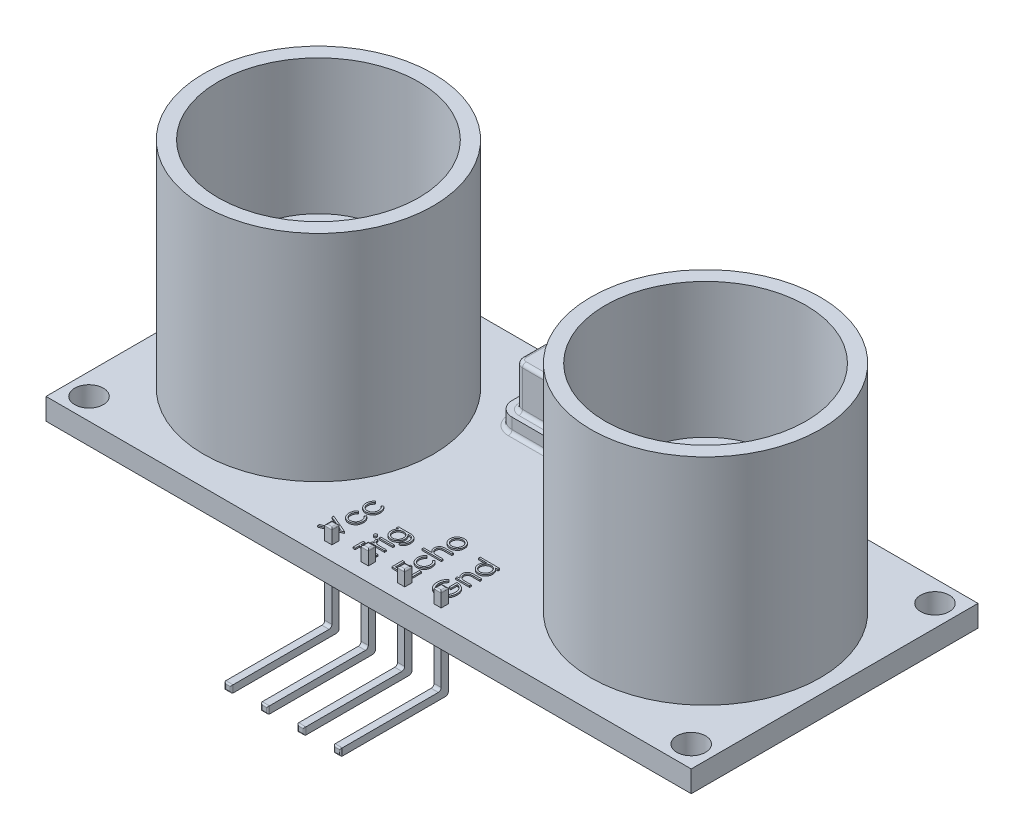
SolidWorks part; units mm, degrees
ref_plane "Front Plane" through (0, 0, 0) normal (0, 0, 1) x (1, 0, 0)
ref_plane "Top Plane" through (0, 0, 0) normal (0, 1, 0) x (1, 0, 0)
ref_plane "Right Plane" through (0, 0, 0) normal (1, 0, 0) x (0, 0, -1)
sketch "Sketch1" plane through (0, 0, 0) normal (0, 1, 0) x (1, 0, 0)
  line L0 (0, 10) -> (45, 10) construction
  line L1 (0, 0) -> (45, 0)
  line L2 (0, 0) -> (0, 20)
  line L3 (0, 20) -> (45, 20)
  line L4 (45, 0) -> (45, 20)
  line L5 (22.5, 20) -> (22.5, 0) construction
  circle A0 centre (1.5, 18.5) radius 1
  circle A1 centre (43.5, 18.5) radius 1
  circle A2 centre (43.5, 1.5) radius 1
  circle A3 centre (1.5, 1.5) radius 1
  dimension "D3" = 2
  dimension "D4" = 1.5
  dimension "D5" = 1.5
  dimension "D1" = 20
  dimension "D2" = 45
extrude "Boss-Extrude1" add sketch "Sketch1" along normal blind 1.5
sketch "Sketch2" plane through (0, 1.5, 0) normal (0, 1, 0) x (1, 0, 0)
  line L0 (45, 20) -> (0, 20) construction
  line L1 (18.5, 19) -> (26.5, 19)
  line L2 (17.5, 18) -> (17.5, 15)
  line L3 (18.5, 14) -> (26.5, 14)
  line L4 (27.5, 18) -> (27.5, 15)
  line L5 (22.5, 20) -> (22.5, 0) construction
  line L6 (0, 0) -> (45, 0) construction
  arc A0 (27.5, 18) -> (26.5, 19) centre (26.5, 18) ccw
  arc A1 (26.5, 14) -> (27.5, 15) centre (26.5, 15) ccw
  arc A2 (17.5, 15) -> (18.5, 14) centre (18.5, 15) ccw
  arc A3 (18.5, 19) -> (17.5, 18) centre (18.5, 18) ccw
  point P15 (22.5, 19)
  dimension "D1" = 1
  dimension "D2" = 10
  dimension "D3" = 5
  dimension "D4" = 1
extrude "Boss-Extrude2" add sketch "Sketch2" along normal blind 1
sketch "Sketch4" plane through (0, 2.5, 0) normal (0, 1, 0) x (1, 0, 0)
  line L1 (18.6475, 18.4133) -> (26.3525, 18.4133)
  line L2 (18.1475, 17.9133) -> (18.1475, 15.0867)
  line L3 (18.6475, 14.5867) -> (26.3525, 14.5867)
  line L4 (26.8525, 17.9133) -> (26.8525, 15.0867)
  line L5 (22.5, 19) -> (22.5, 14) construction
  line L6 (18.5, 19) -> (26.5, 19) construction
  line L7 (18.5, 14) -> (26.5, 14) construction
  line L8 (17.5, 16.5) -> (27.5, 16.5) construction
  line L9 (17.5, 18) -> (17.5, 15) construction
  line L10 (27.5, 18) -> (27.5, 15) construction
  arc A0 (26.3525, 18.4133) -> (26.8525, 17.9133) centre (26.3525, 17.9133) cw
  arc A1 (26.8525, 15.0867) -> (26.3525, 14.5867) centre (26.3525, 15.0867) cw
  arc A2 (18.6475, 14.5867) -> (18.1475, 15.0867) centre (18.6475, 15.0867) cw
  arc A3 (18.6475, 18.4133) -> (18.1475, 17.9133) centre (18.6475, 17.9133) ccw
  point P10 (22.5, 18.4133)
  point P17 (26.8525, 16.5)
  dimension "D1" = 0.5
extrude "Boss-Extrude3" add sketch "Sketch4" along normal blind 3
fillet "Fillet1" radius 0.25 24 edges at (18.294, 5.5, -14.7331) (18.1475, 5.5, -16.5) (18.294, 5.5, -18.2669) (22.5, 5.5, -18.4133) (26.706, 5.5, -18.2669) (26.8525, 5.5, -16.5) (26.706, 5.5, -14.7331) (17.7929, 1.5, -14.2929) (17.5, 1.5, -16.5) (17.7929, 1.5, -18.7071) (22.5, 1.5, -19) (27.2071, 1.5, -18.7071) (27.5, 1.5, -16.5) (27.2071, 1.5, -14.2929) (18.294, 2.5, -18.2669) (22.5, 2.5, -18.4133) (26.706, 2.5, -18.2669) (26.8525, 2.5, -16.5) (26.706, 2.5, -14.7331) (22.5, 2.5, -14.5867) (18.294, 2.5, -14.7331) (22.5, 5.5, -14.5867) (22.5, 1.5, -14) (18.1475, 2.5, -16.5)
sketch "Sketch5" plane through (0, 1.5, 0) normal (0, 1, 0) x (1, 0, 0)
  line L0 (0, 10) -> (45, 10) construction
  line L1 (0, 20) -> (0, 0) construction
  line L2 (45, 0) -> (45, 20) construction
  line L3 (22.5, 20) -> (22.5, 0) construction
  line L4 (45, 20) -> (0, 20) construction
  line L5 (0, 0) -> (45, 0) construction
  circle A0 centre (9, 10) radius 8
  circle A1 centre (36, 10) radius 8
  dimension "D1" = 16
  dimension "D2" = 9
extrude "Boss-Extrude4" add sketch "Sketch5" along normal blind 15
sketch "Sketch6" plane through (0, 16.5, 0) normal (0, 1, 0) x (1, 0, 0)
  line L0 (1, 10) -> (44, 10) construction
  line L1 (9, 18) -> (9, 2) construction
  line L2 (36, 18) -> (36, 2) construction
  line L3 (22.5, 20) -> (22.5, 0) construction
  line L4 (45, 20) -> (0, 20) construction
  line L5 (0, 0) -> (45, 0) construction
  circle A0 centre (9, 10) radius 8 construction
  circle A1 centre (9, 10) radius 8 construction
  circle A2 centre (36, 10) radius 8 construction
  circle A3 centre (36, 10) radius 8 construction
  circle A4 centre (9, 10) radius 7
  circle A5 centre (36, 10) radius 7
  dimension "D1" = 14
extrude "Cut-Extrude1" cut sketch "Sketch6" along direction (0, -1, 0) on the side against the normal offset from surface (13 mm away) 2
sketch "Sketch7" plane through (0, 3.5, 0) normal (0, 1, 0) x (1, 0, 0)
  line L0 (0, 10) -> (45, 10) construction
  line L1 (0, 20) -> (0, 0) construction
  line L2 (45, 0) -> (45, 20) construction
  line L3 (22.5, 20) -> (22.5, 0) construction
  line L4 (45, 20) -> (0, 20) construction
  line L5 (0, 0) -> (45, 0) construction
  line L6 (9, 17) -> (9, 3) construction
  circle A0 centre (9, 10) radius 7 construction
  circle A1 centre (9, 10) radius 7 construction
  circle A2 centre (9, 10) radius 5
  circle A3 centre (36, 10) radius 5
  dimension "D1" = 10
extrude "Boss-Extrude5" add sketch "Sketch7" along normal blind 5
sketch "Sketch8" plane through (0, 1.5, 0) normal (0, 1, 0) x (1, 0, 0)
  line L0 (22.5, 20) -> (22.5, 0) construction
  line L1 (21.23, 1.5) -> (21.23, 1) construction
  line L2 (20.98, 1.5) -> (21.48, 1.5)
  line L3 (20.98, 1.5) -> (20.98, 1)
  line L4 (20.98, 1) -> (21.48, 1)
  line L5 (45, 20) -> (0, 20) construction
  line L6 (0, 0) -> (45, 0) construction
  line L7 (0, 1) -> (45, 1) construction
  line L8 (0, 20) -> (0, 0) construction
  line L9 (45, 0) -> (45, 20) construction
  line L10 (21.48, 1.5) -> (21.48, 1)
  line L11 (20.98, 1.25) -> (21.48, 1.25) construction
  line L12 (23.52, 1.5) -> (24.02, 1.5)
  line L13 (24.02, 1.5) -> (24.02, 1)
  line L14 (23.52, 1) -> (24.02, 1)
  line L15 (23.52, 1.5) -> (23.52, 1)
  line L16 (26.06, 1.5) -> (26.56, 1.5)
  line L17 (26.56, 1.5) -> (26.56, 1)
  line L18 (26.06, 1) -> (26.56, 1)
  line L19 (26.06, 1.5) -> (26.06, 1)
  line L20 (18.44, 1.5) -> (18.94, 1.5)
  line L21 (18.94, 1.5) -> (18.94, 1)
  line L22 (18.44, 1) -> (18.94, 1)
  line L23 (18.44, 1.5) -> (18.44, 1)
  dimension "D1" = 0.5
  dimension "D2" = 0.5
  dimension "D3" = 1
  dimension "D4" = 1.27
  dimension "D5" = 3
  dimension "D6" = 2
extrude "Boss-Extrude6" add sketch "Sketch8" along normal blind 1 and the other way blind 5.5
sketch "Sketch9" plane through (0, 0, -1) normal (0, 0, 1) x (1, 0, 0)
  line L0 (18.94, -4) -> (18.94, 0) construction
  line L1 (18.44, -4) -> (18.94, -4)
  line L2 (18.44, -4) -> (18.44, -3.5)
  line L3 (18.44, -3.5) -> (18.94, -3.5)
  line L4 (18.94, -4) -> (18.94, -3.5)
extrude "Boss-Extrude7" add sketch "Sketch9" along normal blind 7
pattern_linear "LPattern1" count 4 spacing 2.54 along (1, 0, 0) of "Boss-Extrude7"
fillet "Fillet3" radius 0.2 8 edges at (26.31, -3.5, -1) (23.77, -3.5, -1) (21.23, -3.5, -1) (18.69, -3.5, -1) (18.69, -4, -1.5) (21.23, -4, -1.5) (23.77, -4, -1.5) (26.31, -4, -1.5)
fillet "Fillet2" radius 0.1 32 edges at (26.31, 2.5, -1.5) (26.56, 2.5, -1.25) (26.31, 2.5, -1) (26.06, 2.5, -1.25) (23.77, 2.5, -1.5) (24.02, 2.5, -1.25) (23.77, 2.5, -1) (23.52, 2.5, -1.25) (21.23, 2.5, -1.5) (21.48, 2.5, -1.25) (21.23, 2.5, -1) (20.98, 2.5, -1.25) (18.69, 2.5, -1.5) (18.94, 2.5, -1.25) (18.69, 2.5, -1) (18.44, 2.5, -1.25) (26.31, -3.5, 6) (26.06, -3.75, 6) (26.56, -3.75, 6) (26.31, -4, 6) (23.77, -3.5, 6) (23.52, -3.75, 6) (24.02, -3.75, 6) (23.77, -4, 6) (21.23, -3.5, 6) (20.98, -3.75, 6) (21.48, -3.75, 6) (21.23, -4, 6) (18.69, -3.5, 6) (18.94, -3.75, 6) (18.69, -4, 6) (18.44, -3.75, 6)
sketch "Sketch10" plane through (0, 1.5, 0) normal (0, 1, 0) x (1, 0, 0)
  line L0 (18.69, 1.5) -> (18.69, 11.5) construction
  line L1 (18.44, 1.5) -> (18.94, 1.5) construction
  line L2 (21.23, 1.5) -> (21.23, 11.5) construction
  line L3 (23.77, 1.5) -> (23.77, 11.5) construction
  line L4 (26.31, 1.5) -> (26.31, 11.5) construction
  text T0 "Vcc\r\n" font "Century Gothic" height in points 5
  text T1 "Trig\r\n" font "Century Gothic" height in points 5
  text T2 "Echo\r\n" font "Century Gothic" height in points 5
  text T3 "Gnd\r\n" font "Century Gothic" height in points 5
  dimension "D1" = 10
  dimension "D2" = 4
extrude "Boss-Extrude8" add sketch "Sketch10" along normal blind 0.1
sketch "Sketch11" plane through (0, 1.5, 0) normal (0, 1, 0) x (1, 0, 0)
  line L0 (18.5, 19.25) -> (26.5, 19.25) construction
  line L1 (17.25, 19.25) -> (27.75, 19.25)
  line L2 (17.25, 19.25) -> (17.25, 13.75)
  line L3 (17.25, 13.75) -> (27.75, 13.75)
  line L4 (27.75, 19.25) -> (27.75, 13.75)
  line L5 (17.25, 15) -> (17.25, 18) construction
  line L6 (26.5, 13.75) -> (18.5, 13.75) construction
  line L7 (27.75, 18) -> (27.75, 15) construction
  line L8 (18.44, 1.25) -> (26.56, 1.25) construction
  line L9 (18.44, 1) -> (18.44, 1.5) construction
  line L10 (26.56, 1.5) -> (26.56, 1) construction
  line L11 (18.44, 1.75) -> (26.56, 1.75)
  line L12 (18.44, 0.75) -> (26.56, 0.75)
  line L14 (0, 20) -> (45, 20)
  line L15 (0, 20) -> (0, 0)
  line L16 (0, 0) -> (45, 0)
  line L17 (45, 20) -> (45, 0)
  circle A0 centre (1.5, 18.5) radius 1
  circle A1 centre (1.5, 1.5) radius 1
  circle A2 centre (43.5, 18.5) radius 1
  circle A3 centre (43.5, 1.5) radius 1
  circle A4 centre (9, 10) radius 8
  circle A5 centre (36, 10) radius 8
  circle A6 centre (9, 10) radius 8 construction
  circle A7 centre (36, 10) radius 8 construction
  circle A8 centre (43.5, 18.5) radius 1 construction
  circle A9 centre (43.5, 1.5) radius 1 construction
  circle A10 centre (1.5, 1.5) radius 1 construction
  circle A11 centre (1.5, 18.5) radius 1 construction
  arc A12 (18.44, 1.75) -> (18.44, 0.75) centre (18.44, 1.25) ccw
  arc A13 (26.56, 0.75) -> (26.56, 1.75) centre (26.56, 1.25) ccw
  point P48 (22.5, 1.25)
  dimension "D1" = 1
equation "\"D2@Sketch5\"=16/2 + 1"
equation "\"D1@Sketch6\"= 16 -2 "
equation "\"D4@Sketch8\"=2.54/2"
